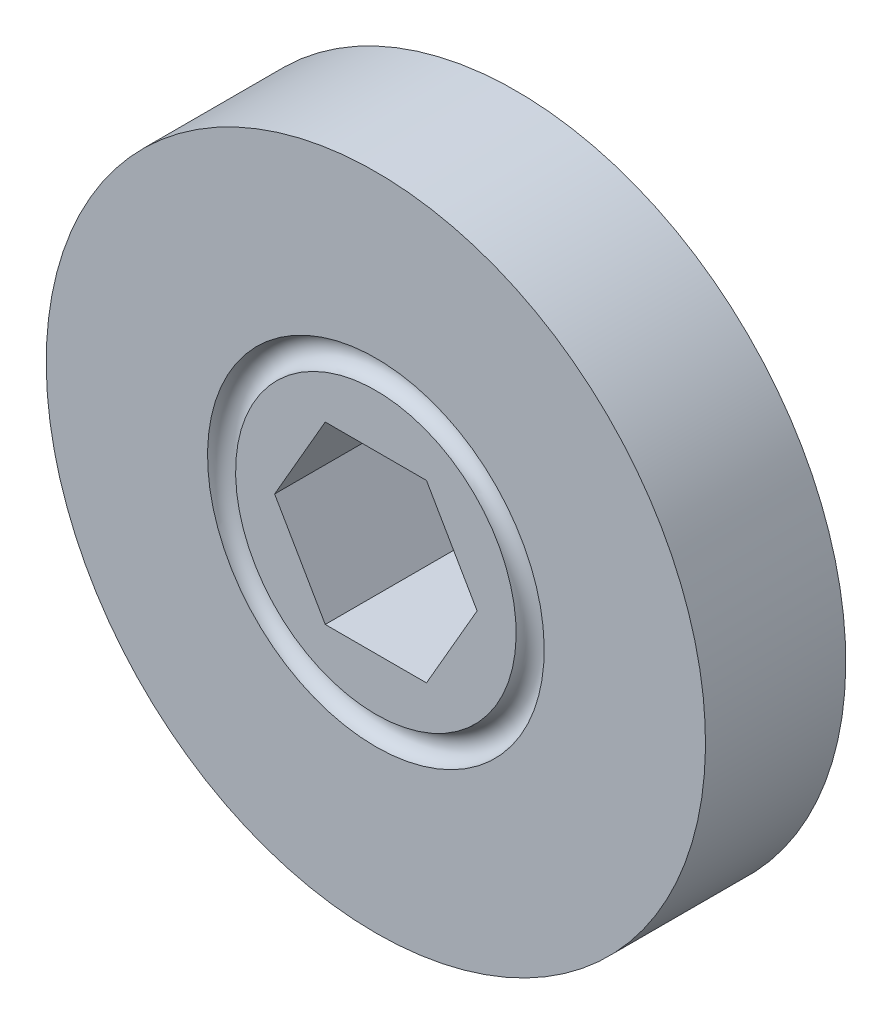
SolidWorks part; units mm, degrees
ref_plane "Front Plane" through (0, 0, 0) normal (0, 0, 1) x (1, 0, 0)
ref_plane "Top Plane" through (0, 0, 0) normal (0, 1, 0) x (1, 0, 0)
ref_plane "Right Plane" through (0, 0, 0) normal (1, 0, 0) x (0, 0, -1)
sketch "Sketch1" plane through (0, 0, 0) normal (1, 0, 0) x (0, 0, -1)
  line L0 (0, 11.938) -> (0, -11.938) construction
  line L1 (-5.08, -11.938) -> (5.08, -11.938)
  line L2 (-5.08, 11.938) -> (5.08, 11.938)
  line L3 (-5.08, 11.938) -> (-5.08, 1.778)
  line L4 (5.08, 11.938) -> (5.08, 1.778)
  line L5 (-5.08, -11.938) -> (-5.08, -0.254)
  line L6 (5.08, -0.254) -> (5.08, -11.938)
  arc A0 (-5.08, 1.778) -> (-5.08, -0.254) centre (-5.08, 0.762) cw
  arc A1 (5.08, 1.778) -> (5.08, -0.254) centre (5.08, 0.762) ccw
  point P4 (0, 0)
  point P7 (0, -11.938)
  point P11 (0, 11.938)
  point P17 (0, 0)
  dimension "D3" = 1.016
  dimension "D1" = 23.876
  dimension "D2" = 10.16
  dimension "D4" = 12.7
revolve "Revolve1" add sketch "Sketch1" angle 360 about L2
sketch "Sketch2" plane through (0, 0, 5.08) normal (0, 0, 1) x (1, 0, 0)
  line L1 (7.3323, 11.938) -> (3.6662, 18.288)
  line L2 (3.6662, 18.288) -> (-3.6662, 18.288)
  line L3 (-3.6662, 18.288) -> (-7.3323, 11.938)
  line L4 (-7.3323, 11.938) -> (-3.6662, 5.588)
  line L5 (-3.6662, 5.588) -> (3.6662, 5.588)
  line L6 (3.6662, 5.588) -> (7.3323, 11.938)
  circle A0 centre (0, 11.938) radius 6.35 construction
  point P1 (0, 11.938)
  point P11 (0, 11.938)
  point P12 (0, 11.938)
  point P13 (0, 0)
  point P15 (0, 11.938)
  point P16 (0, 11.938)
  point P17 (7.3323, 11.938)
  point P18 (0, 0)
  dimension "D1" = 12.7
  dimension "D2" = 11.938
extrude "Cut-Extrude1" cut sketch "Sketch2" against normal up to surface (10.16 mm away) up to face at (0, 1.778, -5.08)
